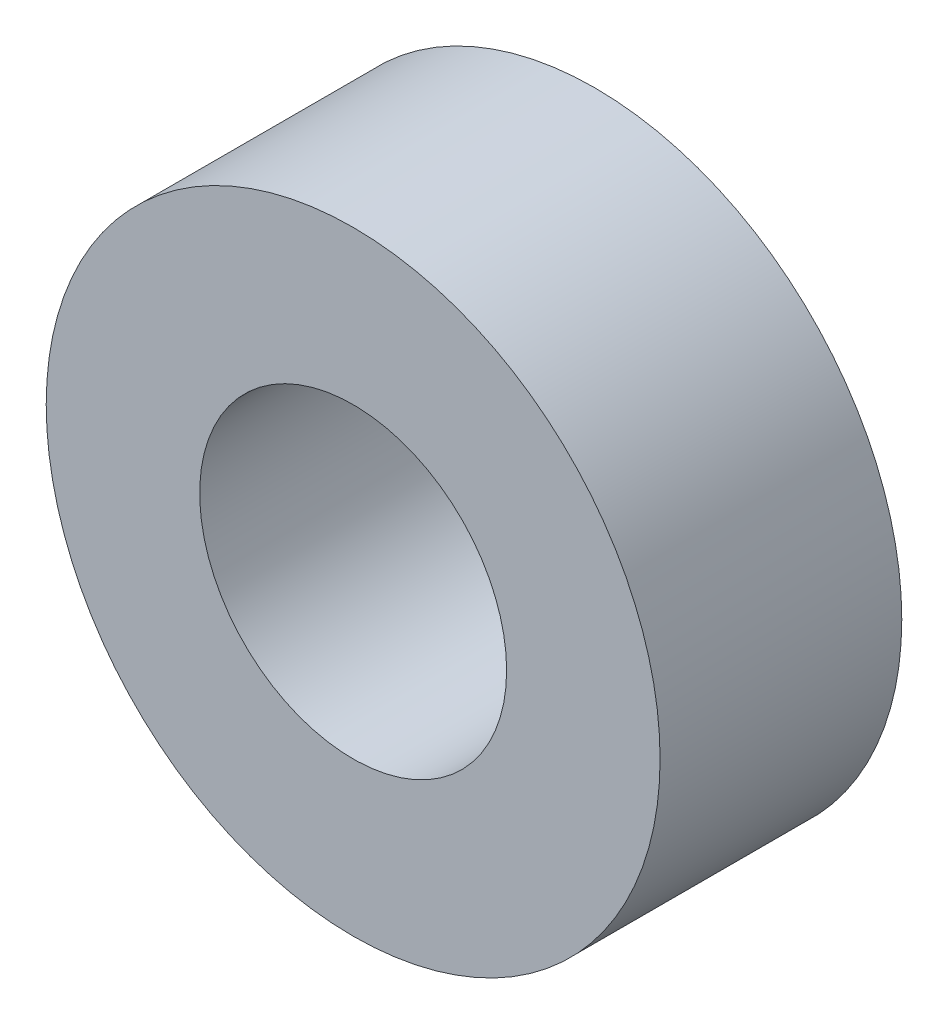
SolidWorks part; units mm, degrees
ref_plane "Alzado" through (0, 0, 0) normal (0, 0, 1) x (1, 0, 0)
ref_plane "Planta" through (0, 0, 0) normal (0, 1, 0) x (1, 0, 0)
ref_plane "Vista lateral" through (0, 0, 0) normal (1, 0, 0) x (0, 0, -1)
sketch "Croquis1" plane through (0, 0, 0) normal (0, 0, 1) x (1, 0, 0)
  circle A0 centre (0, 0) radius 6.35
  circle A1 centre (0, 0) radius 3.175
  dimension "D1" = 12.7
  dimension "D2" = 6.35
extrude "Saliente-Extruir1" add sketch "Croquis1" along normal blind 5
